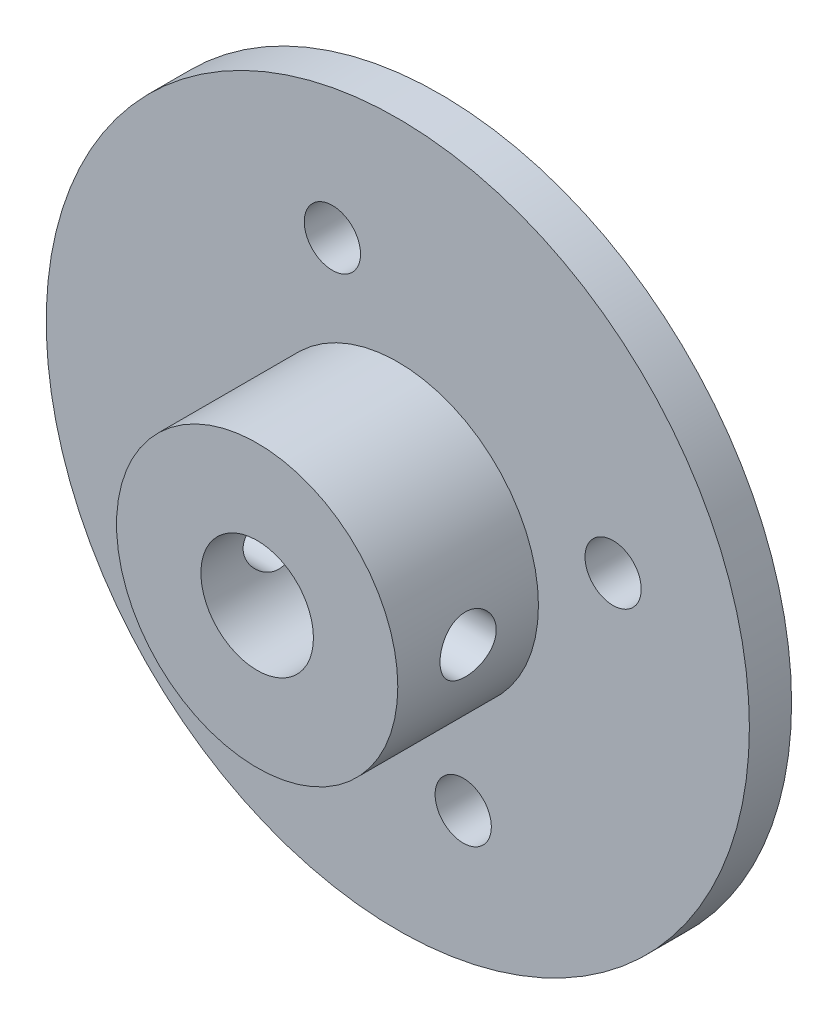
SolidWorks part; units mm, degrees
ref_plane "Alzado" through (0, 0, 0) normal (0, 0, 1) x (1, 0, 0)
ref_plane "Planta" through (0, 0, 0) normal (0, 1, 0) x (1, 0, 0)
ref_plane "Vista lateral" through (0, 0, 0) normal (1, 0, 0) x (0, 0, -1)
sketch "Croquis1" plane through (0, 0, 0) normal (0, 0, 1) x (1, 0, 0)
  circle A0 centre (0, 0) radius 25
  dimension "D1" = 50
extrude "Saliente-Extruir1" add sketch "Croquis1" along normal blind 3
sketch "Croquis2" plane through (0, 0, 3) normal (0, 0, 1) x (1, 0, 0)
  circle A0 centre (0, 0) radius 10
  dimension "D1" = 20
extrude "Saliente-Extruir2" add sketch "Croquis2" along normal blind 10
sketch "Croquis3" plane through (0, 0, 13) normal (0, 0, 1) x (1, 0, 0)
  circle A0 centre (0, 0) radius 4
  dimension "D1" = 8
extrude "Cortar-Extruir1" cut sketch "Croquis3" against normal through all
sketch "Croquis4" plane through (0, 0, 3) normal (0, 0, 1) x (1, 0, 0)
  circle A0 centre (-4.6517, 15.3089) radius 2
  circle A1 centre (15.3089, 4.6517) radius 2
  circle A2 centre (4.6517, -15.3089) radius 2
  circle A3 centre (-15.3089, -4.6517) radius 2
  point P2 (-6.4499, 17.5194)
  point P3 (-4.8936, 16.783)
  point P4 (0, 0)
  point P11 (0, 0)
  point P13 (-4.6179, 15.1978)
  dimension "D2" = 4
  dimension "D3" = 16
  dimension "D1" = 4
extrude "Cortar-Extruir2" cut sketch "Croquis4" against normal through all
sketch "Croquis5" plane through (0, 0, 0) normal (1, 0, 0) x (0, 0, -1)
  line L0 (-13, 0) -> (-3, 0) construction
  line L1 (-13, 10) -> (-13, -10) construction
  line L2 (-3, 10) -> (-13, 10) construction
  line L3 (-13, -10) -> (-3, -10) construction
  line L4 (-3, 10) -> (-3, -10) construction
  circle A0 centre (-8, 0) radius 2
  dimension "D1" = 4
extrude "Cortar-Extruir3" cut sketch "Croquis5" against normal through all and the other way through all
